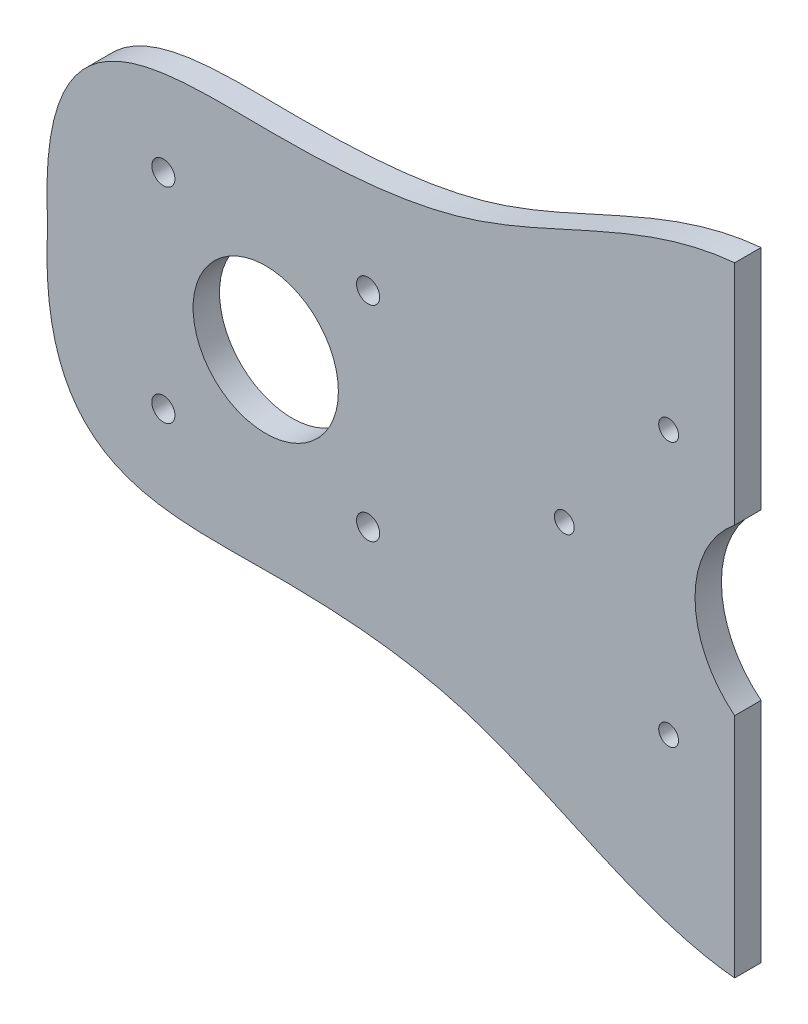
SolidWorks part; units mm, degrees
ref_plane "Front Plane" through (0, 0, 0) normal (0, 0, 1) x (1, 0, 0)
ref_plane "Top Plane" through (0, 0, 0) normal (0, 1, 0) x (1, 0, 0)
ref_plane "Right Plane" through (0, 0, 0) normal (1, 0, 0) x (0, 0, -1)
sketch "Sketch1" plane through (0, 0, 0) normal (0, 0, 1) x (1, 0, 0)
  line L0 (0, 0) -> (-135.6248, 0) construction
  line L1 (-10, -12.49) -> (-10, -46.8924)
  line L2 (-102, 21) -> (-60, 21) construction
  line L3 (-102, 21) -> (-102, -21) construction
  line L4 (-102, -21) -> (-60, -21) construction
  line L5 (-60, 21) -> (-60, -21) construction
  line L6 (-102, 21) -> (-60, -21) construction
  line L7 (-102, -21) -> (-60, 21) construction
  line L8 (-10, 46.8924) -> (-10, 12.49)
  circle A0 centre (0, 0) radius 46.5 construction
  circle A1 centre (0, 0) radius 60 construction
  circle A2 centre (-96.5, 15.5) radius 1.75
  circle A3 centre (-65.5, 15.5) radius 1.75
  circle A4 centre (-65.5, -15.5) radius 1.75
  circle A5 centre (-96.5, -15.5) radius 1.75
  circle A6 centre (-81, 0) radius 11
  circle A7 centre (-35.7878, 0) radius 1.5
  circle A8 centre (-20, 20) radius 1.5
  circle A9 centre (-20, -20) radius 1.5
  arc A10 (-10, 12.49) -> (-10, -12.49) centre (0, 0) ccw
  spline S0 degree 3 poles (-10, 46.8924) (-14.3692, 46.4901) (-28.1676, 42.8611) (-50.0999, 30.0607) (-86.9614, 27.9227) (-115.7833, 30.8075) (-114.0085, 0) knots 0.072782 0.072782 0.072782 0.072782 0.171379 0.397324 0.628336 1 1 1 1
  spline S1 degree 3 poles (-10, -46.8924) (-14.3692, -46.4901) (-28.1676, -42.8611) (-50.0999, -30.0607) (-86.9614, -27.9227) (-115.7833, -30.8075) (-114.0085, 0) knots 0.072782 0.072782 0.072782 0.072782 0.171379 0.397324 0.628336 1 1 1 1
  point P4 (-81, 0)
  dimension "D1" = 93
  dimension "D5" = 120
  dimension "D6" = 3.5
  dimension "D7" = 22
  dimension "D9" = 3
  dimension "D14" = 3
  dimension "D16" = 32
  dimension "D2" = 42
  dimension "D3" = 42
  dimension "D4" = 60
  dimension "D8" = 31
  dimension "D10" = 10
  dimension "D11" = 93.7849
  dimension "D12" = 46.8924
  dimension "D13" = 10
  dimension "D15" = 40
extrude "Boss-Extrude1" add sketch "Sketch1" along normal blind 4
